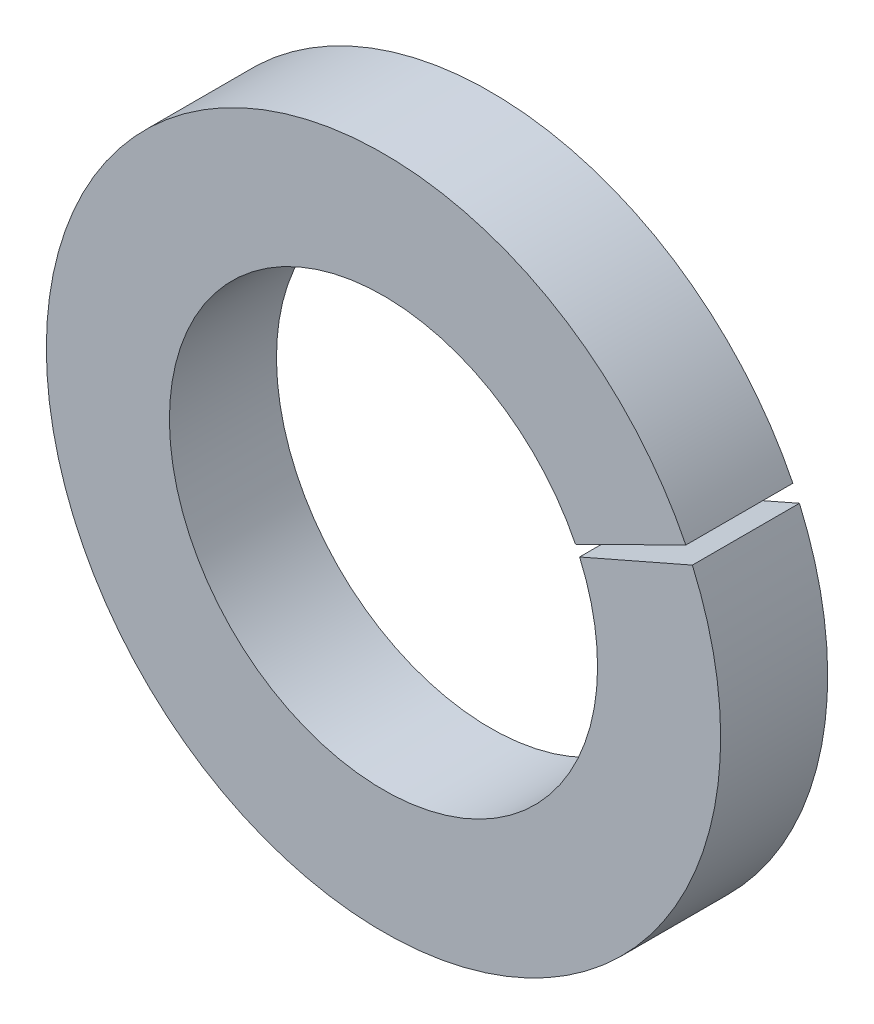
SolidWorks part; units mm, degrees
ref_plane "前视基准面" through (0, 0, 0) normal (0, 0, 1) x (1, 0, 0)
ref_plane "上视基准面" through (0, 0, 0) normal (0, 1, 0) x (1, 0, 0)
ref_plane "右视基准面" through (0, 0, 0) normal (1, 0, 0) x (0, 0, -1)
sketch "草图1" plane through (0, 0, 0) normal (0, 0, 1) x (1, 0, 0)
  circle A0 centre (0, 0) radius 3.15
  circle A1 centre (0, 0) radius 2
  dimension "D1" = 4
  dimension "D2" = 6.3
extrude "凸台-拉伸1" add sketch "草图1" along normal blind 1
sketch "草图2" plane through (0, 0, 1) normal (0, 0, 1) x (1, 0, 0)
  line L0 (0, 0) -> (4.8125, 2.3756)
  line L1 (4.8125, 2.3756) -> (4.8125, 2.1059)
  line L2 (4.8125, 2.1059) -> (0, 0)
extrude "切除-拉伸1" cut sketch "草图2" against normal blind 10
sketch "草图4" plane through (0, 0, 0) normal (0, 0, -1) x (-1, 0, 0)
  circle A0 centre (0, 0) radius 2.05
